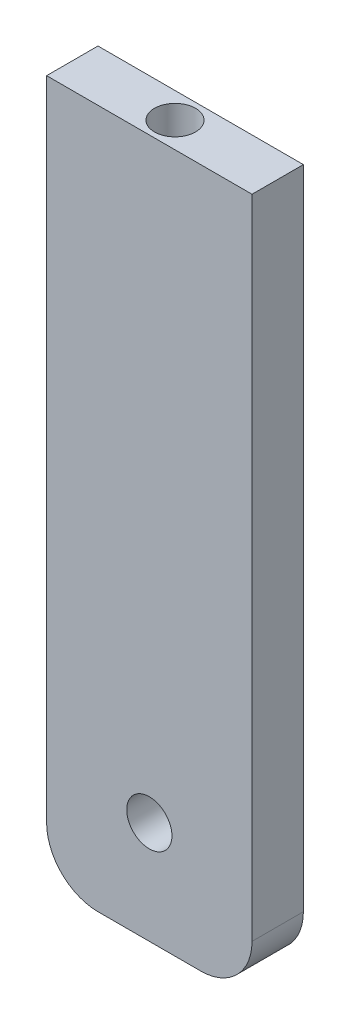
SolidWorks part; units mm, degrees
ref_plane "Front Plane" through (0, 0, 0) normal (0, 0, 1) x (1, 0, 0)
ref_plane "Top Plane" through (0, 0, 0) normal (0, 1, 0) x (1, 0, 0)
ref_plane "Right Plane" through (0, 0, 0) normal (1, 0, 0) x (0, 0, -1)
sketch "ｽｹｯﾁ1" plane through (0, 0, 0) normal (0, 0, 1) x (1, 0, 0)
  line L0 (20, 68) -> (20, 0)
  line L1 (0, 0) -> (20, 0)
  line L2 (0, 0) -> (0, 68)
  line L3 (0, 68) -> (20, 68)
  line L5 (20, 0) -> (0, 0) construction
  line L6 (20, 0) -> (20, 20) construction
  line L7 (20, 20) -> (0, 20) construction
  line L8 (0, 0) -> (0, 20) construction
  line L9 (10, 20) -> (10, 0) construction
  line L10 (20, 10) -> (0, 10) construction
  circle A1 centre (10, 10) radius 2.2
  point P193 (10, 10)
  dimension "D1" = 4.4
  dimension "D3" = 20
extrude "ﾎﾞｽ - 押し出し1" add sketch "ｽｹｯﾁ1" along normal blind 5
fillet "ﾌｨﾚｯﾄ1" radius 5 2 edges at (0, 0, 2.5) (20, 0, 2.5)
sketch "ｽｹｯﾁ2" plane through (0, 68, 0) normal (0, 1, 0) x (1, 0, 0)
  line L0 (20, -5) -> (20, 0) construction
  line L1 (20, -5) -> (0, -5) construction
  circle A0 centre (10, -2.5) radius 2
  point P4 (20, -2.5)
  point P7 (10, -5)
  dimension "D1" = 4
extrude "ｶｯﾄ - 押し出し1" cut sketch "ｽｹｯﾁ2" against normal blind 10
